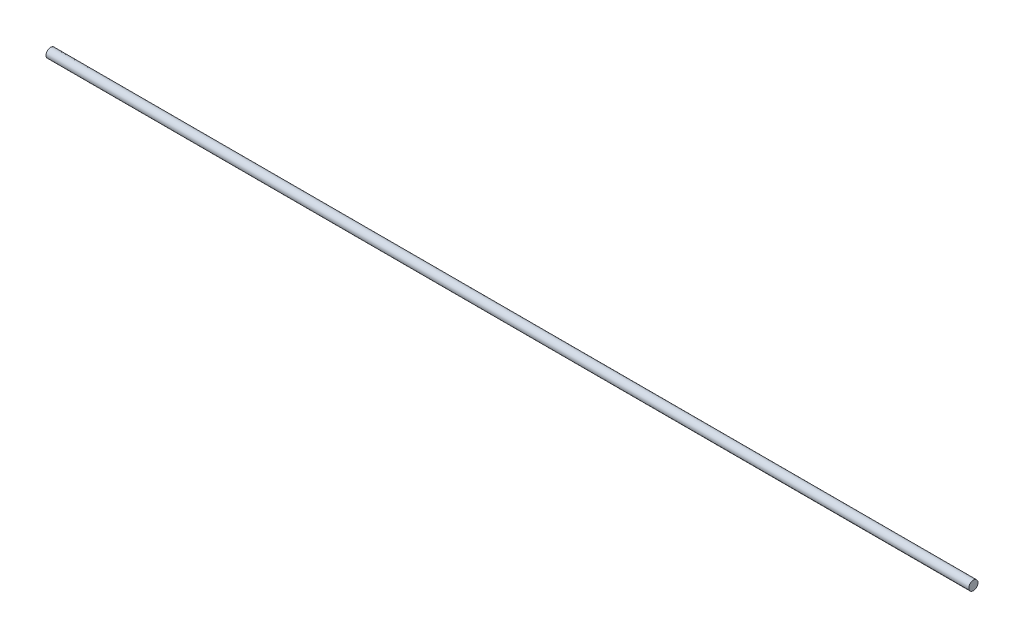
SolidWorks part; units mm, degrees
ref_plane "Front Plane" through (0, 0, 0) normal (0, 0, 1) x (1, 0, 0)
ref_plane "Top Plane" through (0, 0, 0) normal (0, 1, 0) x (1, 0, 0)
ref_plane "Right Plane" through (0, 0, 0) normal (1, 0, 0) x (0, 0, -1)
sketch "Sketch1" plane through (0, 0, 0) normal (1, 0, 0) x (0, 0, -1)
  circle A0 centre (0, 0) radius 4
  dimension "D1" = 8
extrude "Boss-Extrude1" add sketch "Sketch1" along normal blind 800
